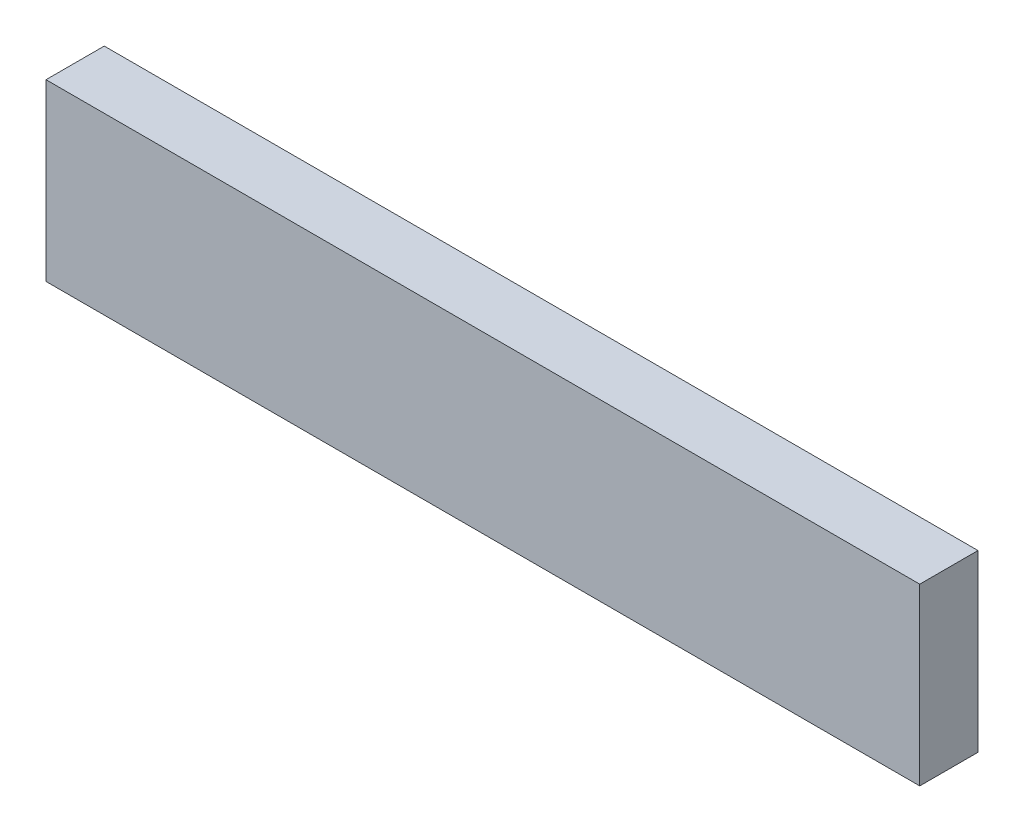
SolidWorks part; units mm, degrees
ref_plane "Front Plane" through (0, 0, 0) normal (0, 0, 1) x (1, 0, 0)
ref_plane "Top Plane" through (0, 0, 0) normal (0, 1, 0) x (1, 0, 0)
ref_plane "Right Plane" through (0, 0, 0) normal (1, 0, 0) x (0, 0, -1)
sketch "Sketch1" plane through (0, 0, 0) normal (0, 0, 1) x (1, 0, 0)
  line L1 (-22.5, 4.5) -> (22.5, 4.5)
  line L2 (-22.5, 4.5) -> (-22.5, -4.5)
  line L3 (-22.5, -4.5) -> (22.5, -4.5)
  line L4 (22.5, 4.5) -> (22.5, -4.5)
  line L5 (-22.5, 4.5) -> (22.5, -4.5) construction
  line L6 (-22.5, -4.5) -> (22.5, 4.5) construction
  point P0 (0, 0)
  dimension "D1" = 9
  dimension "D2" = 45
extrude "Boss-Extrude1" add sketch "Sketch1" along normal blind 3
